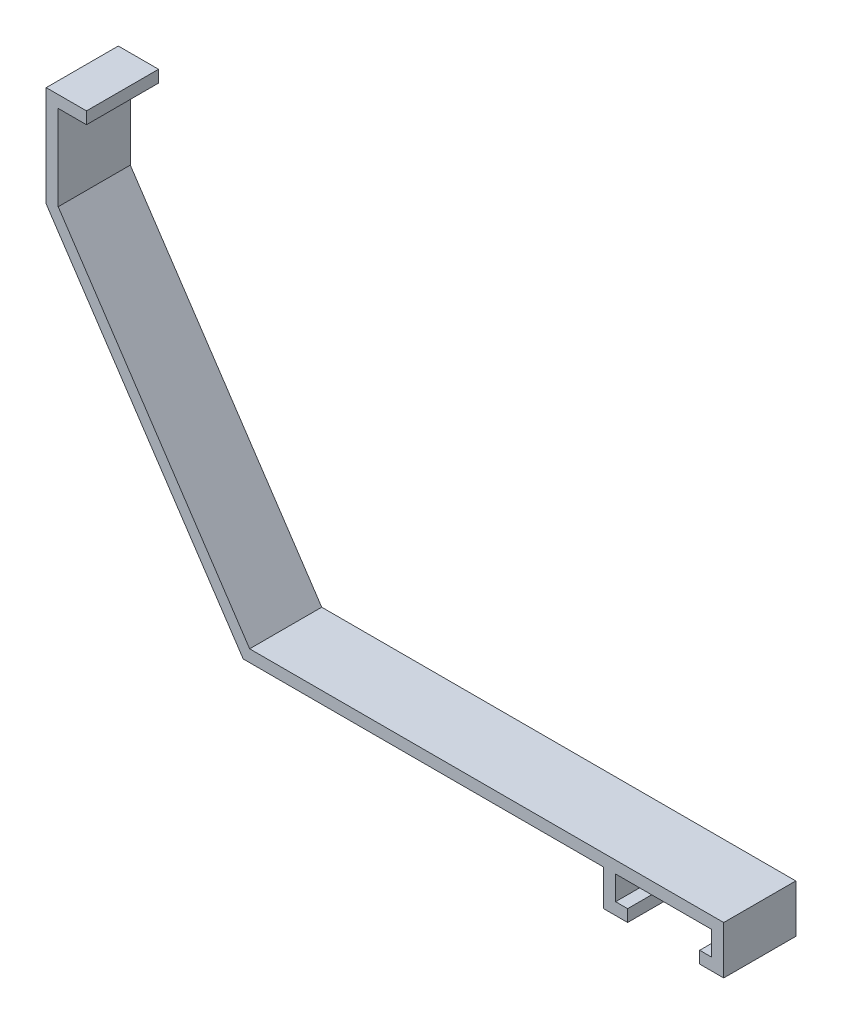
SolidWorks part; units mm, degrees
ref_plane "Front Plane" through (0, 0, 0) normal (0, 0, 1) x (1, 0, 0)
ref_plane "Top Plane" through (0, 0, 0) normal (0, 1, 0) x (1, 0, 0)
ref_plane "Right Plane" through (0, 0, 0) normal (1, 0, 0) x (0, 0, -1)
sketch "Sketch1" plane through (0, 0, 0) normal (0, 0, 1) x (1, 0, 0)
  line L0 (0, 0) -> (-5.3213, 0)
  line L1 (-5.3213, 0) -> (-5.3213, -13.3192)
  line L2 (-5.3213, -13.3192) -> (20.7153, -52.3741)
  line L3 (20.7153, -52.3741) -> (68.3403, -52.3741)
  line L4 (68.3403, -52.3741) -> (68.3403, -57.1366)
  line L5 (68.3403, -57.1366) -> (71.5153, -57.1366)
  line L6 (71.5153, -57.1366) -> (71.5153, -55.5491)
  line L7 (71.5153, -55.5491) -> (69.9278, -55.5491)
  line L8 (69.9278, -55.5491) -> (69.9278, -52.3741)
  line L9 (69.9278, -52.3741) -> (82.6278, -52.3741)
  line L10 (82.6278, -52.3741) -> (82.6278, -55.5491)
  line L11 (82.6278, -55.5491) -> (81.0403, -55.5491)
  line L12 (81.0403, -55.5491) -> (81.0403, -57.1366)
  line L13 (81.0403, -57.1366) -> (84.2153, -57.1366)
  line L14 (84.2153, -57.1366) -> (84.2153, -50.7866)
  line L15 (84.2153, -50.7866) -> (21.5649, -50.7866)
  line L16 (21.5649, -50.7866) -> (-3.7338, -12.8385)
  line L17 (-3.7338, -12.8385) -> (-3.7338, -1.5875)
  line L18 (-3.7338, -1.5875) -> (0, -1.5875)
  line L19 (0, -1.5875) -> (0, 0)
  dimension "D1" = 1.5875
  dimension "D2" = 1.5875
  dimension "D3" = 1.5875
  dimension "D4" = 1.5875
  dimension "D5" = 1.5875
  dimension "D6" = 123.69
  dimension "D7" = 63.5
  dimension "D8" = 11.251
  dimension "D9" = 45.6079
  dimension "D10" = 3.7338
  dimension "D11" = 3.175
  dimension "D12" = 12.7
extrude "Boss-Extrude1" add sketch "Sketch1" along normal blind 9.525
